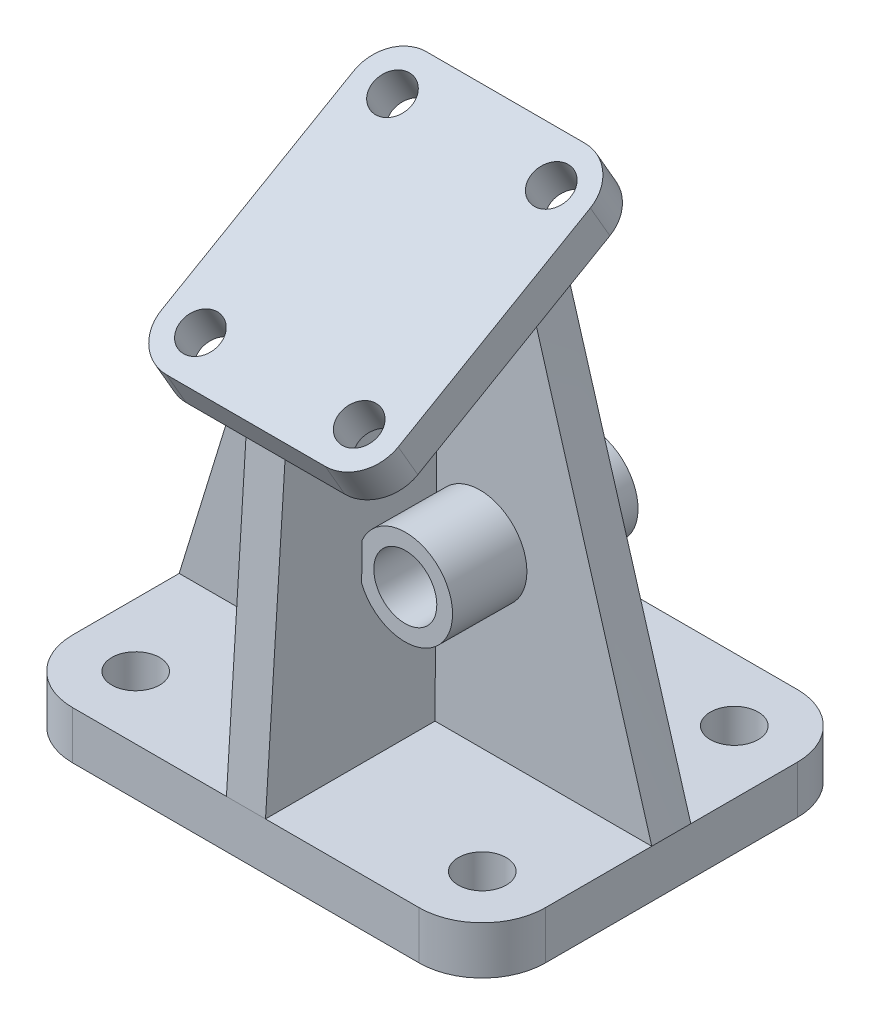
SolidWorks part; units mm, degrees
ref_plane "Front Plane" through (0, 0, 0) normal (0, 0, 1) x (1, 0, 0)
ref_plane "Top Plane" through (0, 0, 0) normal (0, 1, 0) x (1, 0, 0)
ref_plane "Right Plane" through (0, 0, 0) normal (1, 0, 0) x (0, 0, -1)
sketch "Sketch7" plane through (0, 0, 0) normal (0, 1, 0) x (1, 0, 0)
  line L0 (-47.625, 0) -> (47.625, 0) construction
  line L1 (-34.925, 38.1) -> (34.925, 38.1)
  line L2 (-47.625, 25.4) -> (-47.625, -25.4)
  line L3 (-34.925, -38.1) -> (34.925, -38.1)
  line L4 (47.625, 25.4) -> (47.625, -25.4)
  line L5 (-47.625, 38.1) -> (47.625, -38.1) construction
  line L6 (-47.625, -38.1) -> (47.625, 38.1) construction
  line L7 (0, 38.1) -> (0, -38.1) construction
  arc A0 (34.925, 38.1) -> (47.625, 25.4) centre (34.925, 25.4) cw
  arc A1 (-47.625, -25.4) -> (-34.925, -38.1) centre (-34.925, -25.4) ccw
  arc A2 (-34.925, 38.1) -> (-47.625, 25.4) centre (-34.925, 25.4) ccw
  arc A3 (34.925, -38.1) -> (47.625, -25.4) centre (34.925, -25.4) ccw
  circle A4 centre (-34.925, 25.4) radius 4.826
  circle A5 centre (34.925, 25.4) radius 4.826
  circle A6 centre (34.925, -25.4) radius 4.826
  circle A7 centre (-34.925, -25.4) radius 4.826
  point P0 (0, 0)
  dimension "D3" = 12.7
  dimension "D4" = 9.652
  dimension "D1" = 76.2
  dimension "D2" = 95.25
extrude "Boss-Extrude2" add sketch "Sketch7" against normal blind 9.652
sketch "Sketch10" plane through (0, 0, 0) normal (1, 0, 0) x (0, 0, -1)
  line L0 (-38.1, 0) -> (-38.1, 67.564) construction
  line L1 (-38.1, 67.564) -> (14.253, 97.79) construction
  dimension "D1" = 67.564
  dimension "D2" = 120
  dimension "D3" = 60.452
ref_plane "Plane1" through (0, 67.1708, 38.7811) normal (0, -0.866, -0.5) x (0, 0.5, -0.866)
sketch "Sketch11" plane through (0, 67.1708, 38.7811) normal (0, -0.866, -0.5) x (0, 0.5, -0.866)
  line L0 (31.0124, -23.876) -> (31.0124, 23.876) construction
  line L1 (53.3644, -23.876) -> (8.6604, -23.876)
  line L2 (61.2384, -16.002) -> (61.2384, 16.002)
  line L3 (53.3644, 23.876) -> (8.6604, 23.876)
  line L4 (0.7864, -16.002) -> (0.7864, 16.002)
  line L5 (61.2384, -23.876) -> (0.7864, 23.876) construction
  line L6 (61.2384, 23.876) -> (0.7864, -23.876) construction
  line L7 (0.7864, 0) -> (61.2384, 0) construction
  arc A0 (8.6604, -23.876) -> (0.7864, -16.002) centre (8.6604, -16.002) cw
  arc A1 (61.2384, 16.002) -> (53.3644, 23.876) centre (53.3644, 16.002) ccw
  arc A2 (53.3644, -23.876) -> (61.2384, -16.002) centre (53.3644, -16.002) ccw
  arc A3 (8.6604, 23.876) -> (0.7864, 16.002) centre (8.6604, 16.002) ccw
  circle A4 centre (53.3644, -16.002) radius 3.937
  circle A5 centre (8.6604, -16.002) radius 3.937
  circle A6 centre (53.3644, 16.002) radius 3.937
  circle A7 centre (8.6604, 16.002) radius 3.937
  point P0 (31.0124, 0)
  dimension "D3" = 7.874
  dimension "D4" = 7.874
  dimension "D1" = 60.452
  dimension "D2" = 47.752
extrude "Boss-Extrude3" add sketch "Sketch11" along normal blind 7.874 separate body
sketch "Sketch12" plane through (0, 0, 0) normal (0, 1, 0) x (1, 0, 0)
  line L0 (47.625, -25.4) -> (47.625, 25.4) construction
  line L1 (-47.625, 3.937) -> (47.625, 3.937)
  line L2 (-47.625, 3.937) -> (-47.625, -3.937)
  line L3 (-47.625, -3.937) -> (47.625, -3.937)
  line L4 (47.625, 3.937) -> (47.625, -3.937)
  line L5 (-47.625, 3.937) -> (47.625, -3.937) construction
  line L6 (-47.625, -3.937) -> (47.625, 3.937) construction
  line L7 (-34.925, -38.1) -> (34.925, -38.1) construction
  point P0 (0, 0)
  point P7 (47.625, 0)
  dimension "D1" = 7.874
  dimension "D2" = 38.1
sketch "Sketch13" plane through (0, 0, 0) normal (0, 0, 1) x (1, 0, 0)
  line L0 (47.625, 0) -> (23.876, 80.4689)
  point P3 (0, 0)
  point P4 (0, 0)
sketch "Sketch15" plane through (0, 60.3517, 34.8441) normal (0, -0.866, -0.5) x (1, 0, 0)
  line L0 (-23.876, -8.6604) -> (-23.876, -53.3644) construction
  line L1 (23.876, -36.2975) -> (-23.876, -36.2975)
  line L2 (23.876, -36.2975) -> (23.876, -44.1715)
  line L3 (23.876, -44.1715) -> (-23.876, -44.1715)
  line L4 (-23.876, -36.2975) -> (-23.876, -44.1715)
  line L5 (23.876, -36.2975) -> (-23.876, -44.1715) construction
  line L6 (23.876, -44.1715) -> (-23.876, -36.2975) construction
  point P0 (-42.102, -33.2921)
  dimension "D1" = 7.874
loft "Loft1" add profiles "Sketch15", "Sketch12"
sketch "Sketch16" plane through (0, 0, 0) normal (1, 0, 0) x (0, 0, -1)
  line L0 (-38.1, 0) -> (-34.163, 60.7449)
rib "Rib1" sketch "Sketch16" sketch "Sketch16" thickness 7.874 extrusion direction parallel to sketch draft on no parameters "D1"=7.874
sketch "Sketch17" plane through (0, 0.0265, 3.9368) normal (0, 0.0067, 1) x (1, 0, 0)
  line L0 (3.937, -0.0265) -> (47.625, -0.0265) construction
  circle A0 centre (12.7, 35.0255) radius 9.525
  circle A1 centre (12.7, 35.0255) radius 6.35
  dimension "D1" = 19.05
  dimension "D4" = 12.7
  dimension "D2" = 35.052
  dimension "D3" = 12.7
extrude "Boss-Extrude4" add sketch "Sketch17" along normal blind 14.986
sketch "Sketch18" plane through (0, 0.0252, -3.9368) normal (0, 0.0064, -1) x (-1, 0, 0)
  line L0 (-34.925, -0.2438) -> (34.925, -0.2438) construction
  circle A0 centre (-12.7, 34.8082) radius 9.525
  circle A1 centre (-12.7, 34.8082) radius 6.35
  dimension "D3" = 19.05
  dimension "D4" = 12.7
  dimension "D1" = 35.052
  dimension "D2" = 12.7
extrude "Boss-Extrude5" add sketch "Sketch18" along normal blind 14.986
